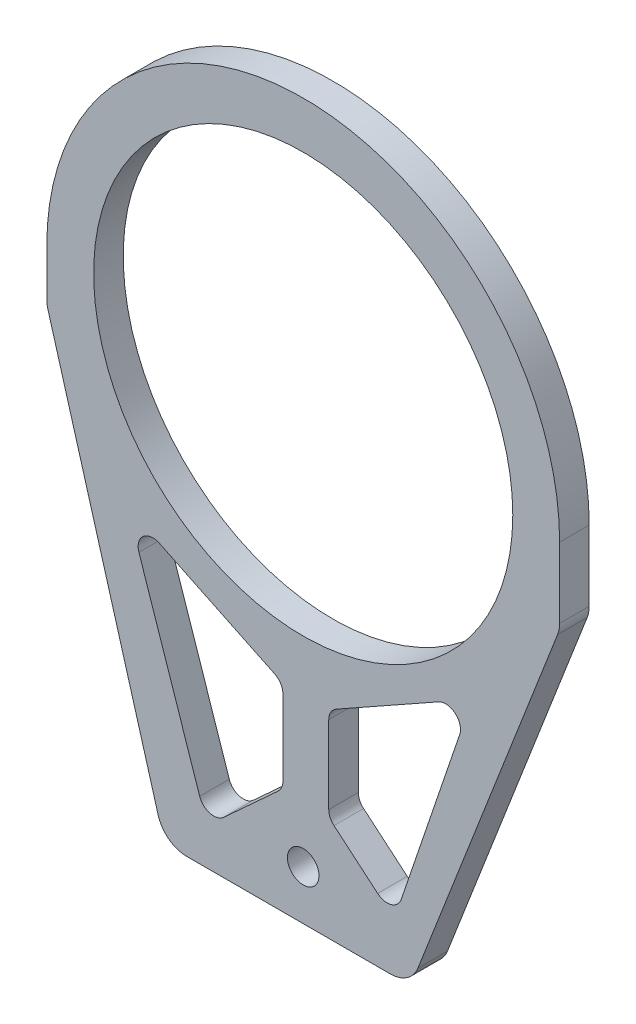
SolidWorks part; units mm, degrees
material "Thornel Mat VMA"
ref_plane "前视基准面" through (0, 0, 0) normal (0, 0, 1) x (1, 0, 0)
ref_plane "上视基准面" through (0, 0, 0) normal (0, 1, 0) x (1, 0, 0)
ref_plane "右视基准面" through (0, 0, 0) normal (1, 0, 0) x (0, 0, -1)
sketch "草图1" plane through (0, 0, 0) normal (0, 0, 1) x (1, 0, 0)
  line L0 (-26, 0) -> (-26, -46.5)
  line L1 (-26, -46.5) -> (26, -46.5)
  line L2 (26, -46.5) -> (26, 0)
  circle A0 centre (0, 0) radius 21.25
  arc A1 (-26, 0) -> (26, 0) centre (0, 0) cw
  dimension "D1" = 42.5
  dimension "D2" = 26
  dimension "D3" = 46.5
extrude "凸台-拉伸1" add sketch "草图1" along normal blind 3
sketch "草图2" plane through (0, 0, 3) normal (0, 0, 1) x (1, 0, 0)
  line L0 (-26, -46.5) -> (26, -46.5) construction
  line L1 (0, -41.5) -> (0, -46.5) construction
  circle A0 centre (0, -41.5) radius 1.6
  dimension "D2" = 3.2
  dimension "D5" = 5
extrude "切除-拉伸1" cut sketch "草图2" against normal blind 3
sketch "草图3" plane through (0, 0, 3) normal (0, 0, 1) x (1, 0, 0)
  line L0 (-26, -5.1045) -> (-14.0753, -46.5)
  line L1 (-26, 0) -> (-26, -46.5) construction
  line L2 (-26, -46.5) -> (26, -46.5) construction
  line L3 (-14.0753, -46.5) -> (-26, -46.5)
  line L4 (-26, -46.5) -> (-26, -5.1045)
  line L5 (26, -7.6939) -> (10.8885, -46.5)
  line L6 (26, -46.5) -> (26, 0) construction
  line L7 (10.8885, -46.5) -> (26, -46.5)
  line L8 (26, -46.5) -> (26, -7.6939)
  line L9 (-17.7933, -18.8479) -> (-2.0582, -26.4167)
  line L10 (-2.0582, -26.4167) -> (-2.0582, -35.6889)
  line L11 (-2.0582, -35.6889) -> (-9.7598, -42.7494)
  line L12 (-9.7598, -42.7494) -> (-17.7933, -18.8479)
  line L13 (17.1294, -18.2504) -> (2.5893, -26.4167)
  line L14 (2.5893, -26.4167) -> (2.5893, -35.8772)
  line L15 (2.5893, -35.8772) -> (9.2286, -41.4879)
  line L16 (9.2286, -41.4879) -> (17.1294, -18.2504)
  point P21 (17.1294, -18.2504)
  point P23 (10.0917, -39.6953)
  point P24 (4.5147, -37.5043)
  point P25 (9.2286, -41.4879)
  point P26 (3.5188, -27.6782)
  point P27 (-10.0254, -40.0937)
  point P28 (-3.1205, -36.6627)
  point P29 (-9.7598, -42.7494)
  point P30 (-17.7933, -18.8479)
  point P31 (-2.0582, -26.4167)
  point P32 (2.5893, -26.4167)
extrude "切除-拉伸2" cut sketch "草图3" against normal through all
fillet "圆角1" radius 1.5 8 edges at (9.2286, -41.4879, 1.5) (2.5893, -35.8772, 1.5) (2.5893, -26.4167, 1.5) (17.1294, -18.2504, 1.5) (-2.0582, -26.4167, 1.5) (-2.0582, -35.6889, 1.5) (-9.7598, -42.7494, 1.5) (-17.7933, -18.8479, 1.5)
fillet "圆角2" radius 3 4 edges at (26, -7.6939, 1.5) (-26, -5.1045, 1.5) (-14.0753, -46.5, 1.5) (10.8885, -46.5, 1.5)
